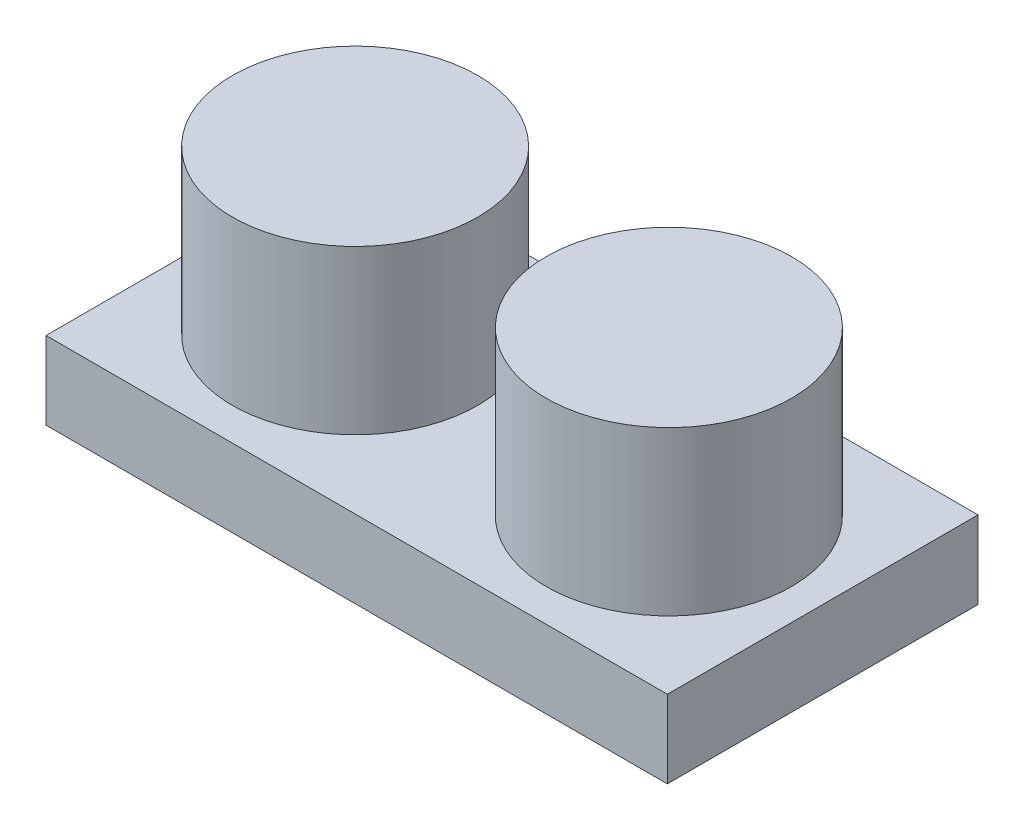
SolidWorks part; units mm, degrees
ref_plane "Front Plane" through (0, 0, 0) normal (0, 0, 1) x (1, 0, 0)
ref_plane "Top Plane" through (0, 0, 0) normal (0, 1, 0) x (1, 0, 0)
ref_plane "Right Plane" through (0, 0, 0) normal (1, 0, 0) x (0, 0, -1)
sketch "Sketch1" plane through (0, 0, 0) normal (0, 1, 0) x (1, 0, 0)
  line L1 (-20, 10) -> (20, 10)
  line L2 (-20, 10) -> (-20, -10)
  line L3 (-20, -10) -> (20, -10)
  line L4 (20, 10) -> (20, -10)
  line L5 (-20, 10) -> (20, -10) construction
  line L6 (-20, -10) -> (20, 10) construction
  point P0 (0, 0)
  dimension "D1" = 20
  dimension "D2" = 40
extrude "Boss-Extrude1" add sketch "Sketch1" along normal blind 5
sketch "Sketch2" plane through (0, 5, 0) normal (0, 1, 0) x (1, 0, 0)
  line L0 (-20, 10) -> (-20, -10) construction
  line L1 (20, -10) -> (20, 10) construction
  circle A0 centre (-10.1, 0) radius 7.9
  circle A1 centre (10.1, 0) radius 7.9
  point P6 (0, 0)
  point P7 (0, 0)
  point P11 (0, 0)
  dimension "D1" = 15.8
  dimension "D2" = 9.9
  dimension "D3" = 15.8
  dimension "D4" = 9.9
extrude "Boss-Extrude2" add sketch "Sketch2" along normal blind 10.5
